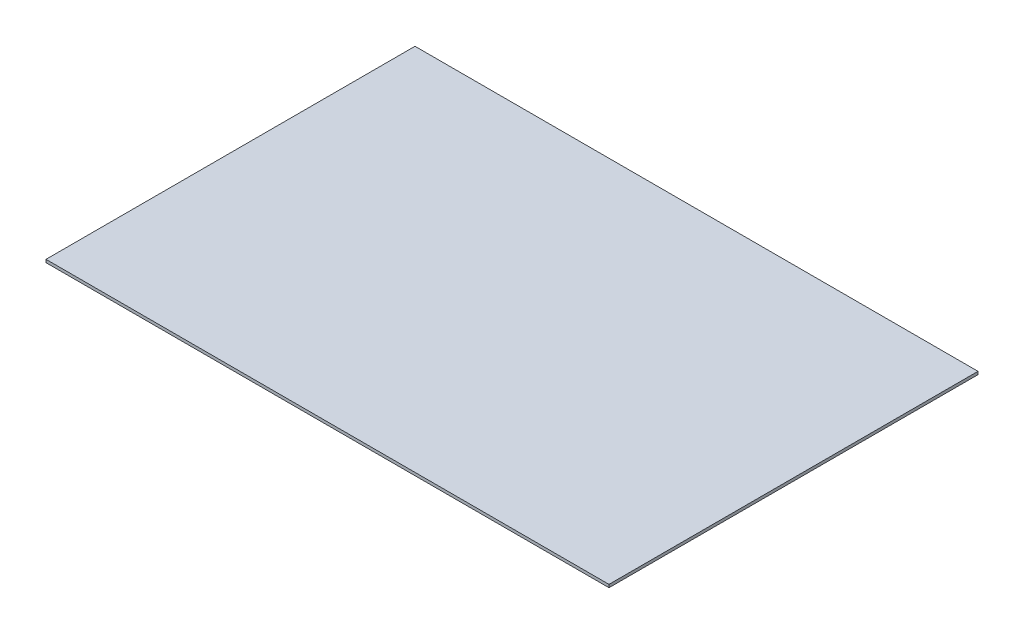
SolidWorks part; units mm, degrees
ref_plane "Front Plane" through (0, 0, 0) normal (0, 0, 1) x (1, 0, 0)
ref_plane "Top Plane" through (0, 0, 0) normal (0, 1, 0) x (1, 0, 0)
ref_plane "Right Plane" through (0, 0, 0) normal (1, 0, 0) x (0, 0, -1)
sketch "Sketch1" plane through (0, 0, 0) normal (0, 1, 0) x (1, 0, 0)
  line L1 (-195, 127.5) -> (191, 127.5)
  line L2 (-195, 127.5) -> (-195, -125.5)
  line L3 (-195, -125.5) -> (191, -125.5)
  line L4 (191, 127.5) -> (191, -125.5)
extrude "Boss-Extrude1" add sketch "Sketch1" along normal blind 2
